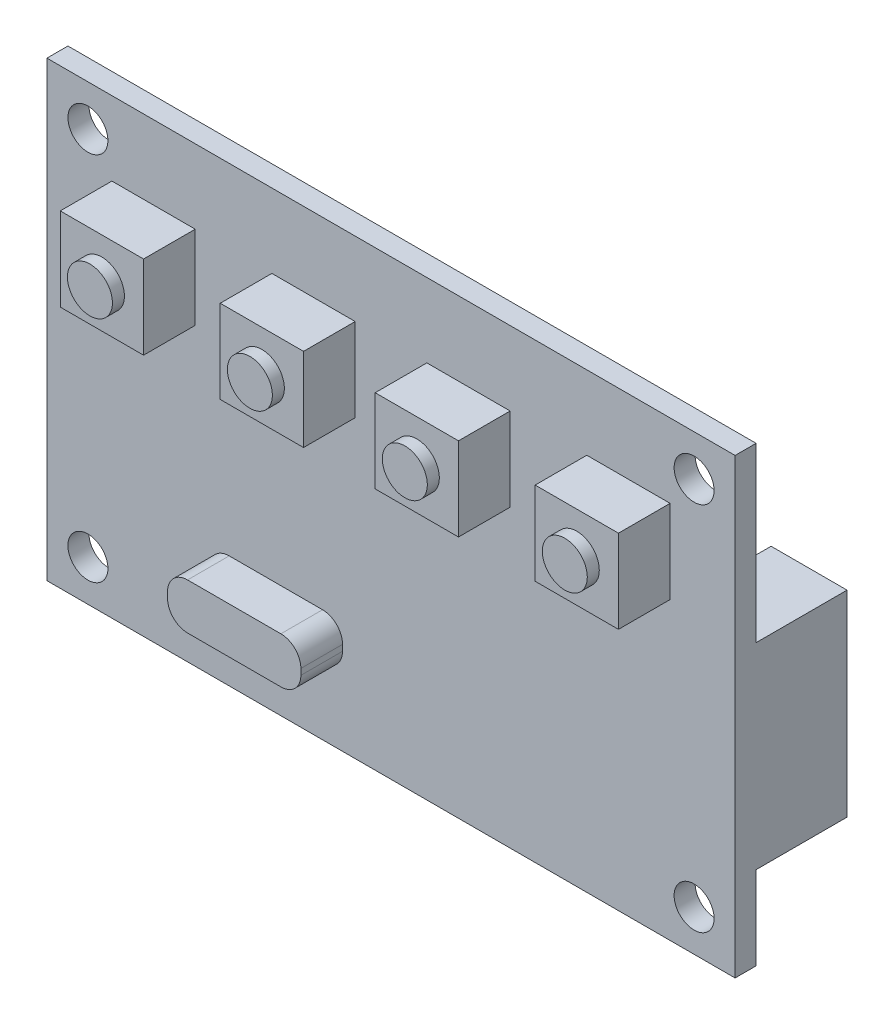
SolidWorks part; units mm, degrees
ref_plane "Front Plane" through (0, 0, 0) normal (0, 0, 1) x (1, 0, 0)
ref_plane "Top Plane" through (0, 0, 0) normal (0, 1, 0) x (1, 0, 0)
ref_plane "Right Plane" through (0, 0, 0) normal (1, 0, 0) x (0, 0, -1)
sketch "Sketch1" plane through (0, 0, 0) normal (0, 0, 1) x (1, 0, 0)
  line L0 (0, 0) -> (0, 9.8032) construction
  line L1 (-26.2255, 17.2466) -> (26.2255, 17.2466)
  line L2 (-26.2255, 17.2466) -> (-26.2255, -17.2466)
  line L3 (-26.2255, -17.2466) -> (26.2255, -17.2466)
  line L4 (26.2255, 17.2466) -> (26.2255, -17.2466)
  line L5 (-26.2255, 17.2466) -> (26.2255, -17.2466) construction
  line L6 (-26.2255, -17.2466) -> (26.2255, 17.2466) construction
  line L7 (0, 0) -> (10.4588, 0) construction
  circle A0 centre (23.1013, 14.1224) radius 1.524
  circle A2 centre (23.1013, -14.1224) radius 1.524
  circle A3 centre (-23.1013, -14.1224) radius 1.524
  circle A4 centre (-23.1013, 14.1224) radius 1.524
  point P0 (0, 0)
  dimension "D3" = 3.048
  dimension "D4" = 1.6002
  dimension "D5" = 1.6002
  dimension "D1" = 52.451
  dimension "D2" = 34.4932
extrude "Boss-Extrude1" add sketch "Sketch1" along normal blind 1.6002
sketch "Sketch2" plane through (0, 0, 1.6002) normal (0, 0, 1) x (1, 0, 0)
  line L0 (0, 0) -> (0, 7.7532) construction
  line L1 (-21.2725, 11.6078) -> (-14.9225, 11.6078)
  line L2 (-21.2725, 11.6078) -> (-21.2725, 5.2578)
  line L3 (-21.2725, 5.2578) -> (-14.9225, 5.2578)
  line L4 (-14.9225, 11.6078) -> (-14.9225, 5.2578)
  line L5 (26.2255, 17.2466) -> (-26.2255, 17.2466) construction
  line L6 (-26.2255, 17.2466) -> (-26.2255, -17.2466) construction
  line L7 (-9.0805, 11.6078) -> (-9.0805, 5.2578)
  line L8 (-9.0805, 11.6078) -> (-2.7305, 11.6078)
  line L9 (-2.7305, 11.6078) -> (-2.7305, 5.2578)
  line L10 (-9.0805, 5.2578) -> (-2.7305, 5.2578)
  line L11 (21.2725, 5.2578) -> (14.9225, 5.2578)
  line L12 (14.9225, 11.6078) -> (14.9225, 5.2578)
  line L13 (21.2725, 11.6078) -> (14.9225, 11.6078)
  line L14 (21.2725, 11.6078) -> (21.2725, 5.2578)
  line L15 (9.0805, 11.6078) -> (2.7305, 11.6078)
  line L16 (2.7305, 11.6078) -> (2.7305, 5.2578)
  line L17 (9.0805, 5.2578) -> (2.7305, 5.2578)
  line L18 (9.0805, 11.6078) -> (9.0805, 5.2578)
  dimension "D1" = 6.35
  dimension "D2" = 6.35
  dimension "D3" = 5.6388
  dimension "D4" = 4.953
  dimension "D5" = 2
extrude "Boss-Extrude2" add sketch "Sketch2" along normal blind 3.937
sketch "Sketch3" plane through (0, 0, 1.6002) normal (0, 0, 1) x (1, 0, 0)
  line L0 (-26.2255, -17.2466) -> (26.2255, -17.2466) construction
  line L1 (-12.3317, -8.6614) -> (-5.2197, -8.6614)
  line L2 (-13.8557, -10.1854) -> (-13.8557, -10.6426)
  line L3 (-12.3317, -12.1666) -> (-5.2197, -12.1666)
  line L4 (-3.6957, -10.1854) -> (-3.6957, -10.6426)
  line L5 (-26.2255, 17.2466) -> (-26.2255, -17.2466) construction
  arc A0 (-13.8557, -10.1854) -> (-12.3317, -8.6614) centre (-12.3317, -10.1854) cw
  arc A1 (-5.2197, -8.6614) -> (-3.6957, -10.1854) centre (-5.2197, -10.1854) cw
  arc A2 (-5.2197, -12.1666) -> (-3.6957, -10.6426) centre (-5.2197, -10.6426) ccw
  arc A3 (-13.8557, -10.6426) -> (-12.3317, -12.1666) centre (-12.3317, -10.6426) ccw
  point P6 (-13.8557, -8.6614)
  point P9 (-3.6957, -8.6614)
  point P14 (-13.8557, -12.1666)
  dimension "D3" = 1.524
  dimension "D4" = 1.524
  dimension "D1" = 10.16
  dimension "D2" = 3.5052
  dimension "D5" = 5.08
  dimension "D6" = 12.3698
extrude "Boss-Extrude3" add sketch "Sketch3" along normal blind 3.175
sketch "Sketch4" plane through (0, 0, 0) normal (0, 0, -1) x (-1, 0, 0)
  line L6 (0, 0) -> (0, 9.5184) construction
  line L12 (-20.4343, -10.8966) -> (-26.2255, -10.8966)
  line L13 (-26.2255, 4.0894) -> (-26.2255, -10.8966)
  line L14 (-20.4343, 4.0894) -> (-26.2255, 4.0894)
  line L15 (-20.4343, 4.0894) -> (-20.4343, -10.8966)
  line L16 (26.2255, -4.2418) -> (20.4343, -4.2418)
  line L17 (20.4343, 8.2042) -> (20.4343, -4.2418)
  line L18 (26.2255, 8.2042) -> (20.4343, 8.2042)
  line L19 (26.2255, 8.2042) -> (26.2255, -4.2418)
  line L21 (26.2255, -17.2466) -> (-26.2255, -17.2466) construction
  line L22 (-26.2255, -17.2466) -> (-26.2255, 17.2466) construction
  line L23 (-26.2255, 17.2466) -> (26.2255, 17.2466) construction
  dimension "D1" = 14.986
  dimension "D2" = 5.7912
  dimension "D3" = 6.35
  dimension "D4" = 0
  dimension "D5" = 5.7912
  dimension "D6" = 12.446
  dimension "D7" = 9.0424
extrude "Boss-Extrude4" add sketch "Sketch4" along normal blind 6.9342
sketch "Sketch5" plane through (0, 0, 0) normal (0, 0, -1) x (-1, 0, 0)
  line L7 (12.2555, -7.4168) -> (7.1755, -7.4168)
  line L8 (7.1755, 5.2832) -> (7.1755, -7.4168)
  line L9 (12.2555, 5.2832) -> (7.1755, 5.2832)
  line L10 (12.2555, 5.2832) -> (12.2555, -7.4168)
  line L11 (-26.2255, 17.2466) -> (26.2255, 17.2466) construction
  dimension "D1" = 5.08
  dimension "D2" = 12.7
  dimension "D3" = 11.9634
extrude "Boss-Extrude5" add sketch "Sketch5" along normal blind 11.938
sketch "Sketch6" plane through (0, 0, 5.5372) normal (0, 0, 1) x (1, 0, 0)
  circle A0 centre (-18.0975, 8.4328) radius 1.7145
  circle A4 centre (-5.9055, 8.4328) radius 1.7145
  circle A5 centre (5.9055, 8.4328) radius 1.7145
  circle A6 centre (18.0975, 8.4328) radius 1.7145
  dimension "D1" = 3.429
  dimension "D3" = 3.429
  dimension "D2" = 2
  dimension "D4" = 2
extrude "Boss-Extrude6" add sketch "Sketch6" along normal blind 0.9144 contours A4 | A0 | A5 | A6
